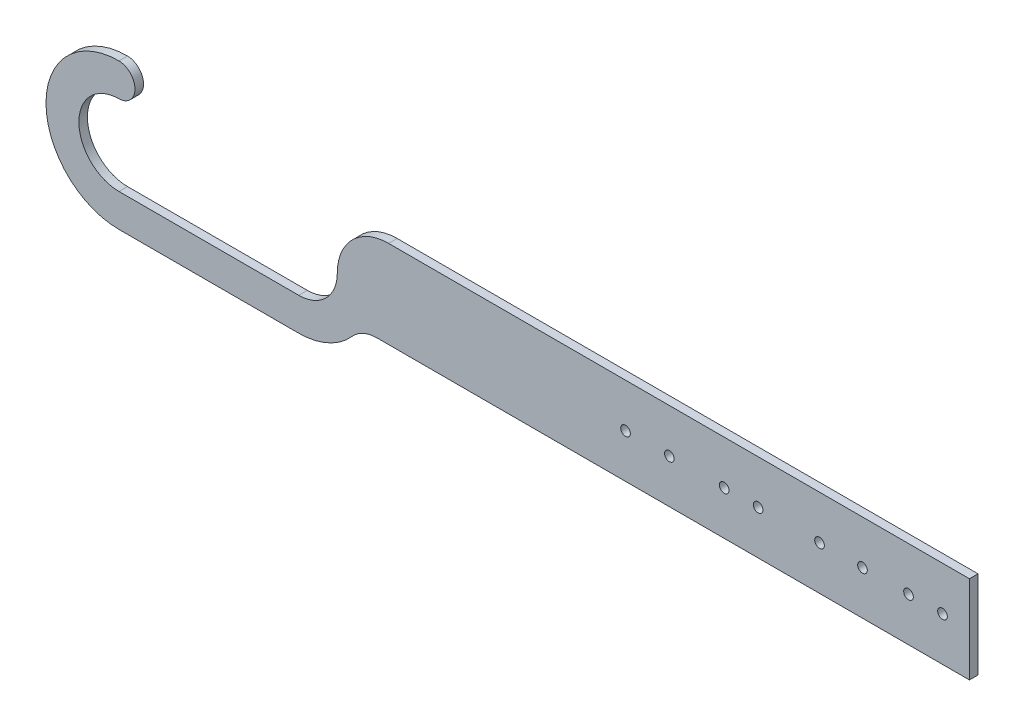
SolidWorks part; units mm, degrees
ref_plane "Front Plane" through (0, 0, 0) normal (0, 0, 1) x (1, 0, 0)
ref_plane "Top Plane" through (0, 0, 0) normal (0, 1, 0) x (1, 0, 0)
ref_plane "Right Plane" through (0, 0, 0) normal (1, 0, 0) x (0, 0, -1)
sketch "Sketch1" plane through (0, 0, 0) normal (0, 0, 1) x (1, 0, 0)
  line L0 (9.7117, -12.5656) -> (-62.4546, -12.5656)
  line L1 (-41.5092, 38.2344) -> (295.0408, 38.2344)
  line L2 (-41.5092, 38.2344) -> (-41.5092, -12.5656)
  line L3 (-41.5092, -12.5656) -> (295.0408, -12.5656)
  line L4 (295.0408, 38.2344) -> (295.0408, -12.5656)
  line L5 (-71.2272, 8.5164) -> (-71.2272, -12.5656)
  line L6 (-71.2272, -12.5656) -> (-62.4546, -12.5656)
  circle A0 centre (-41.5092, 8.5164) radius 29.718
  dimension "D3" = 21.082
  dimension "D1" = 50.8
  dimension "D2" = 336.55
extrude "Boss-Extrude1" add sketch "Sketch1" along normal blind 4.953 contours L2 A0 L0 | A0 L0 L3 L4 L1 | L3 A0 L2 | A0 L5 L6
sketch "Sketch4" plane through (0, 0, 0) normal (0, 0, -1) x (-1, 0, 0)
  line L0 (93.5792, -13.8356) -> (197.7192, -13.8356)
  line L1 (93.5792, -32.8856) -> (197.7192, -32.8856)
  line L2 (93.5792, -13.8356) -> (197.7192, -13.8356) construction
  line L3 (-295.0408, -12.5656) -> (71.2272, -12.5656) construction
  line L4 (71.2272, 8.5164) -> (71.2272, -12.5656) construction
  line L5 (71.2272, 8.5164) -> (71.2272, -12.5656)
  line L6 (71.2272, -12.5656) -> (48.3701, -12.5656)
  line L7 (206.2697, 31.0179) -> (208.5224, 50.2948)
  line L8 (197.7192, -13.8356) -> (197.7192, -32.8856)
  line L9 (145.6492, -13.8356) -> (145.6492, -32.8856)
  arc A0 (197.7192, -13.8356) -> (197.7192, 32.6479) centre (197.7192, 9.4062) ccw
  arc A1 (197.7192, -32.8856) -> (197.7192, 51.6979) centre (197.7192, 9.4062) ccw
  arc A2 (71.2272, 8.5164) -> (93.5792, -13.8356) centre (93.5792, 8.5164) ccw
  arc A3 (62.6166, -18.9689) -> (93.5792, -32.8856) centre (93.5792, 8.5164) ccw
  arc A4 (52.1772, 8.5164) -> (93.5792, -32.8856) centre (93.5792, 8.5164) ccw construction
  arc A5 (48.3701, -12.5656) -> (62.6166, -18.9689) centre (48.3701, -31.6156) cw
  circle A6 centre (197.9799, 42.1729) radius 9.5286
  dimension "D3" = 19.05
  dimension "D4" = 19.05
  dimension "D6" = 42.2918
  dimension "D2" = 104.14
  dimension "D5" = 20.32
extrude "Boss-Extrude4" add sketch "Sketch4" against normal blind 4.953
sketch "Sketch5" plane through (0, 0, 0) normal (0, 0, -1) x (-1, 0, 0)
  line L0 (-295.0408, 38.2344) -> (-295.0408, -12.5656) construction
  line L2 (-295.0408, 12.8344) -> (70.9118, 12.8344) construction
  circle A0 centre (-279.4198, 12.8344) radius 2.794
  arc A1 (71.2272, 8.5164) -> (41.5092, 38.2344) centre (41.5092, 8.5164) ccw construction
  circle A2 centre (-259.7348, 12.8344) radius 2.794
  circle A3 centre (-233.0648, 12.8344) radius 2.794
  circle A4 centre (-208.1728, 12.8344) radius 2.794
  circle A5 centre (-172.6128, 12.8344) radius 2.794
  circle A6 centre (-152.9278, 12.8344) radius 2.794
  circle A7 centre (-121.1778, 12.8344) radius 2.794
  circle A8 centre (-95.7778, 12.8344) radius 2.794
  dimension "D2" = 5.588
  dimension "D3" = 5.588
  dimension "D4" = 19.685
  dimension "D5" = 26.67
  dimension "D6" = 5.588
  dimension "D7" = 5.588
  dimension "D8" = 24.892
  dimension "D9" = 35.56
  dimension "D10" = 5.588
  dimension "D11" = 19.685
  dimension "D12" = 5.588
  dimension "D13" = 31.75
  dimension "D14" = 5.588
  dimension "D15" = 25.4
  dimension "D16" = 5.588
  dimension "D1" = 15.621
extrude "Cut-Extrude1" cut sketch "Sketch5" against normal blind 4.953
